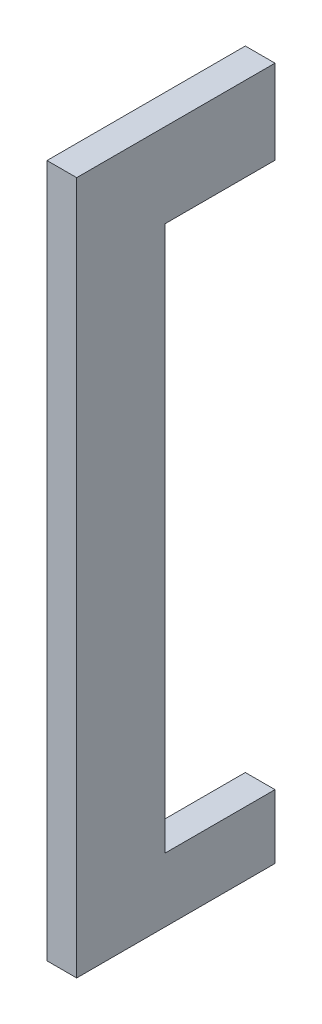
SolidWorks part; units mm, degrees
ref_plane "Front Plane" through (0, 0, 0) normal (0, 0, 1) x (1, 0, 0)
ref_plane "Top Plane" through (0, 0, 0) normal (0, 1, 0) x (1, 0, 0)
ref_plane "Right Plane" through (0, 0, 0) normal (1, 0, 0) x (0, 0, -1)
sketch "Sketch1" plane through (0, 0, 0) normal (1, 0, 0) x (0, 0, -1)
  line L0 (20.0425, 0) -> (20.0425, 6.4639)
  line L1 (0, 0) -> (20.0425, 0)
  line L2 (0, 0) -> (0, 70.0425)
  line L3 (0, 70.0425) -> (20.0425, 70.0425)
  line L5 (20.0425, 6.4639) -> (8.9438, 6.4639)
  line L6 (8.9438, 6.4639) -> (8.9438, 61.5425)
  line L7 (8.9438, 61.5425) -> (20.0425, 61.5425)
  line L8 (20.0425, 61.5425) -> (20.0425, 70.0425)
extrude "Boss-Extrude1" add sketch "Sketch1" along normal blind 3
